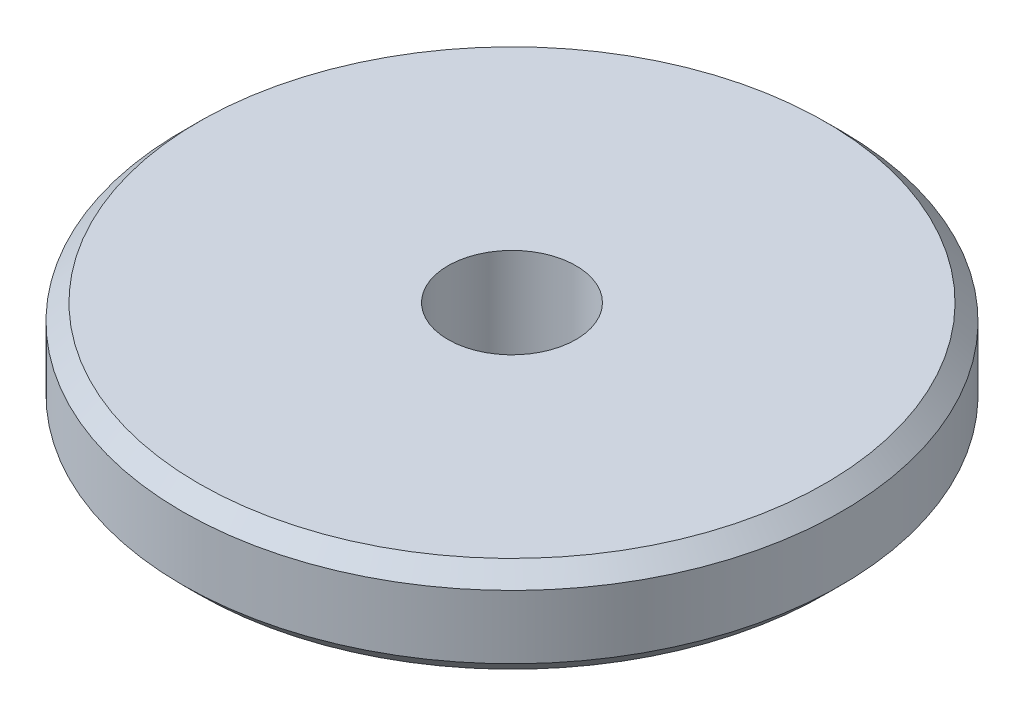
SolidWorks part; units mm, degrees
material "PVC 0.007 Plasticized"
ref_plane "Front Plane" through (0, 0, 0) normal (0, 0, 1) x (1, 0, 0)
ref_plane "Top Plane" through (0, 0, 0) normal (0, 1, 0) x (1, 0, 0)
ref_plane "Right Plane" through (0, 0, 0) normal (1, 0, 0) x (0, 0, -1)
sketch "Sketch1" plane through (0, 0, 0) normal (0, 1, 0) x (1, 0, 0)
  circle A0 centre (0, 0) radius 1
  circle A1 centre (0, 0) radius 5.15
  dimension "D1" = 2
  dimension "D2" = 10.3
extrude "Bed Wheel" add sketch "Sketch1" along normal blind 1.5
chamfer "Chamfer1" distance 0.254 angle 45 2 edges at (0, 1.5, 5.15) (0, 0, 5.15)
